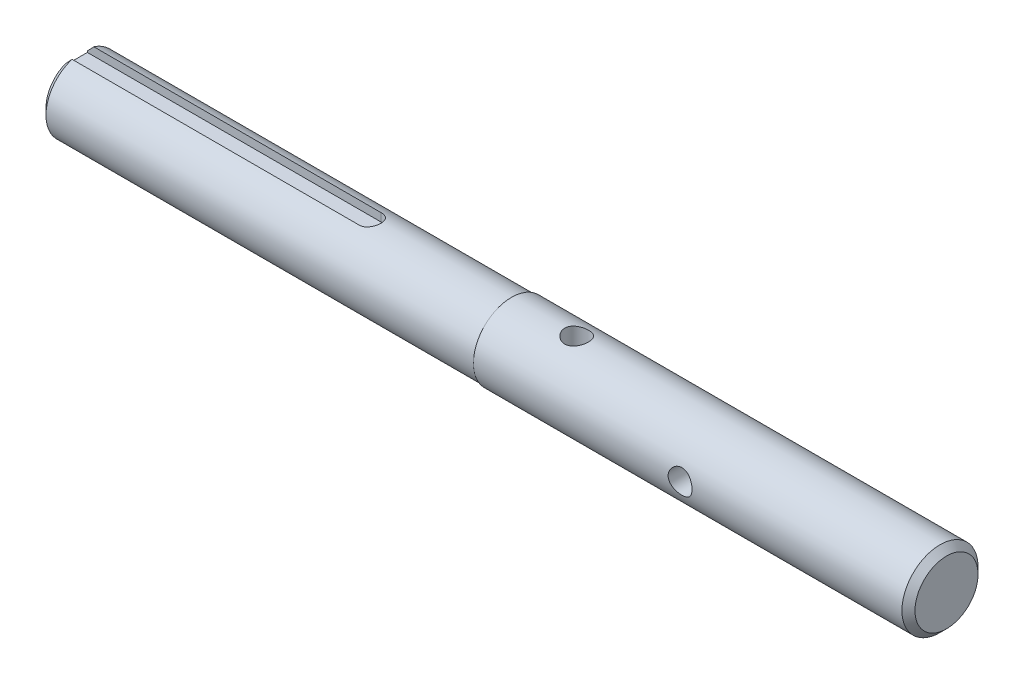
SolidWorks part; units mm, degrees
ref_plane "Front Plane" through (0, 0, 0) normal (0, 0, 1) x (1, 0, 0)
ref_plane "Top Plane" through (0, 0, 0) normal (0, 1, 0) x (1, 0, 0)
ref_plane "Right Plane" through (0, 0, 0) normal (1, 0, 0) x (0, 0, -1)
sketch "Sketch1" plane through (0, 0, 0) normal (0, 0, 1) x (1, 0, 0)
  line L0 (0, 0) -> (400, 0)
  line L1 (400, 0) -> (400, 17.5)
  line L2 (400, 17.5) -> (200, 17.5)
  line L3 (200, 17.5) -> (200, 17)
  line L4 (200, 17) -> (0, 17)
  line L5 (0, 17) -> (0, 0)
  dimension "D1" = 17.5
  dimension "D2" = 17
  dimension "D3" = 400
  dimension "D4" = 200
revolve "Revolve1" add sketch "Sketch1" angle 360 about L0
chamfer "Chamfer1" distance 3 angle 45 2 edges at (0, 0, 17) (400, 0, 17.5)
sketch "Sketch2" plane through (0, 0, 0) normal (0, 1, 0) x (1, 0, 0)
  line L0 (0, 14) -> (0, -14) construction
  line L1 (0, 5) -> (135, 5)
  line L2 (0, 5) -> (0, -5)
  line L3 (0, -5) -> (135, -5)
  line L4 (135, 5) -> (135, -5) construction
  line L5 (0, 5) -> (135, -5) construction
  line L6 (0, -5) -> (135, 5) construction
  arc A0 (135, 5) -> (135, -5) centre (135, 0) cw
  point P4 (67.5, 0)
  dimension "D4" = 5
  dimension "D1" = 135
  dimension "D2" = 5
  dimension "D3" = 10
extrude "Cut-Extrude1" cut sketch "Sketch2" against normal blind 4.5 from offset 17
sketch "Sketch3" plane through (0, 0, 0) normal (0, 1, 0) x (1, 0, 0)
  circle A0 centre (230, 0) radius 5.5
  dimension "D1" = 11
  dimension "D2" = 230
extrude "Cut-Extrude2" cut sketch "Sketch3" against normal through all both and the other way through all
sketch "Sketch4" plane through (0, 0, 0) normal (0, 0, 1) x (1, 0, 0)
  circle A0 centre (295, 0) radius 5.5
  dimension "D1" = 11
  dimension "D2" = 295
extrude "Cut-Extrude3" cut sketch "Sketch4" against normal through all both and the other way through all
